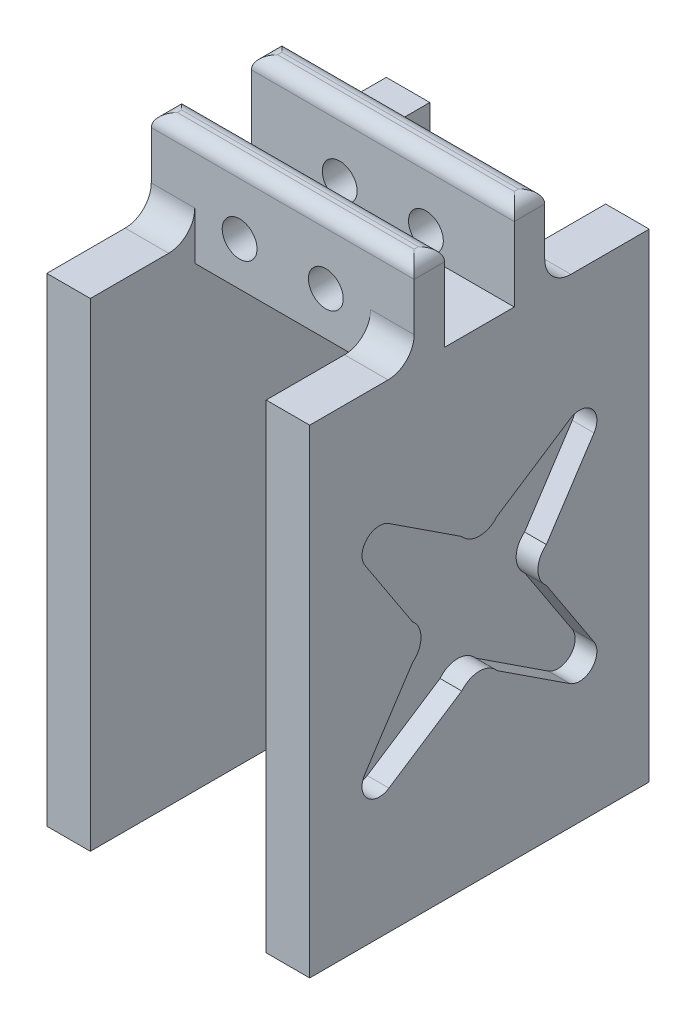
SolidWorks part; units mm, degrees
ref_plane "Front Plane" through (0, 0, 0) normal (0, 0, 1) x (1, 0, 0)
ref_plane "Top Plane" through (0, 0, 0) normal (0, 1, 0) x (1, 0, 0)
ref_plane "Right Plane" through (0, 0, 0) normal (1, 0, 0) x (0, 0, -1)
sketch "Sketch1" plane through (0, 0, 0) normal (1, 0, 0) x (0, 0, -1)
  line L0 (0, 27.5) -> (-4, 32.5) construction
  line L1 (-19.5, -27.5) -> (19.5, -27.5)
  line L2 (-19.5, -27.5) -> (-19.5, 27.5)
  line L3 (-19.5, 27.5) -> (-7.5, 27.5)
  line L4 (19.5, -27.5) -> (19.5, 27.5)
  line L5 (-19.5, -27.5) -> (19.5, 27.5) construction
  line L6 (-19.5, 27.5) -> (19.5, -27.5) construction
  line L8 (4, 27.5) -> (4, 37.5)
  line L9 (4, 37.5) -> (7.5, 37.5)
  line L10 (7.5, 27.5) -> (7.5, 37.5)
  line L12 (-4, 27.5) -> (-4, 37.5)
  line L13 (-4, 37.5) -> (-7.5, 37.5)
  line L14 (-7.5, 27.5) -> (-7.5, 37.5)
  line L15 (0, 27.5) -> (4, 32.5) construction
  line L16 (7.5, 27.5) -> (19.5, 27.5)
  line L17 (-4, 27.5) -> (4, 27.5)
  point P0 (0, 0)
  point P16 (-4.395, 37.5)
  point P18 (0, 0)
  point P19 (-0.3295, 28.4884)
  point P20 (0, 0)
  point P21 (3.6231, 37.5)
  dimension "D1" = 55
  dimension "D2" = 39
  dimension "D3" = 8
  dimension "D4" = 10
  dimension "D5" = 3.5
extrude "Boss-Extrude1" add sketch "Sketch1" along normal mid plane 30.2
sketch "Sketch2" plane through (0, 0, 19.5) normal (0, 0, 1) x (1, 0, 0)
  line L0 (15.1, -27.5) -> (-15.1, -27.5) construction
  line L1 (-10.1, -27.5) -> (10.1, -27.5)
  line L2 (-10.1, -27.5) -> (-10.1, 25)
  line L3 (-10.1, 25) -> (10.1, 25)
  line L4 (10.1, -27.5) -> (10.1, 25)
  line L5 (-10.1, -1.25) -> (-15.1, -1.25) construction
  line L6 (-15.1, 27.5) -> (-15.1, -27.5) construction
  line L7 (10.1, -1.25) -> (15.1, -1.25) construction
  line L8 (15.1, 27.5) -> (15.1, -27.5) construction
  dimension "D1" = 52.5
  dimension "D2" = 20.2
extrude "Cut-Extrude1" cut sketch "Sketch2" against normal up to surface (39 mm away) up to face at (0, 0, -19.5)
sketch "Sketch3" plane through (0, 27.5, 0) normal (0, 1, 0) x (1, 0, 0)
  line L0 (15.1, -19.5) -> (-15.1, -19.5) construction
  line L1 (-10.1, -19.5) -> (10.1, -19.5)
  line L2 (-10.1, -19.5) -> (-10.1, -7.5)
  line L3 (-10.1, -7.5) -> (10.1, -7.5)
  line L4 (10.1, -19.5) -> (10.1, -7.5)
  line L5 (15.1, -7.5) -> (-15.1, -7.5) construction
  line L6 (15.1, 7.5) -> (-15.1, 7.5) construction
  line L7 (-10.1, 7.5) -> (10.1, 7.5)
  line L8 (-10.1, 7.5) -> (-10.1, 19.5)
  line L9 (-10.1, 19.5) -> (10.1, 19.5)
  line L10 (10.1, 7.5) -> (10.1, 19.5)
  line L11 (15.1, 19.5) -> (-15.1, 19.5) construction
  line L12 (-10.1, -13.5) -> (-15.1, -13.5) construction
  line L13 (-15.1, -7.5) -> (-15.1, -19.5) construction
  line L14 (10.1, 13.5) -> (15.1, 13.5) construction
  line L15 (15.1, 19.5) -> (15.1, 7.5) construction
  line L16 (10.1, -13.5) -> (15.1, -13.5) construction
  line L17 (15.1, -7.5) -> (15.1, -19.5) construction
  line L18 (-10.1, 13.5) -> (-15.1, 13.5) construction
  line L19 (-15.1, 19.5) -> (-15.1, 7.5) construction
  dimension "D1" = 5
  dimension "D2" = 5
extrude "Cut-Extrude2" cut sketch "Sketch3" against normal up to surface (2.5 mm away) up to face at (0, 25, 0)
fillet "Fillet1" radius 3 4 edges at (-12.6, 27.5, -7.5) (12.6, 27.5, -7.5) (-12.6, 27.5, 7.5) (12.6, 27.5, 7.5)
fillet "Fillet2" radius 1.5 8 edges at (0, 37.5, -7.5) (15.1, 37.5, -5.75) (0, 37.5, -4) (-15.1, 37.5, -5.75) (0, 37.5, 4) (15.1, 37.5, 5.75) (0, 37.5, 7.5) (-15.1, 37.5, 5.75)
sketch "Sketch4" plane through (0, 0, 7.5) normal (0, 0, 1) x (1, 0, 0)
  line L0 (0, 36) -> (0, 25) construction
  line L1 (15.1, 36) -> (-15.1, 36) construction
  line L2 (-10.1, 25) -> (10.1, 25) construction
  circle A0 centre (-4.95, 30) radius 2
  circle A2 centre (4.95, 30) radius 2
  point P10 (0, 29.9804)
  dimension "D1" = 4
  dimension "D2" = 6
  dimension "D3" = 4.95
extrude "Cut-Extrude3" cut sketch "Sketch4" against normal up to surface (15 mm away) up to face at (0, 30.5, -7.5)
sketch "Sketch5" plane through (15.1, 0, 0) normal (1, 0, 0) x (0, 0, -1)
  line L0 (-12.9047, 12.9047) -> (12.9047, 12.9047) construction
  line L1 (0, 12.9047) -> (0, -12.9047) construction
  line L2 (12.9047, -12.9047) -> (-12.9047, -12.9047) construction
  line L3 (12.9047, 12.9047) -> (12.9047, -12.9047) construction
  line L4 (-7.6857, 2.0288) -> (-2.0288, 7.6857) construction
  line L5 (-12.9047, 12.9047) -> (12.9047, -12.9047) construction
  line L6 (-14.5654, 0) -> (12.9047, 0) construction
  line L7 (13.1637, 10.3949) -> (7.6857, 2.0288)
  line L8 (10.3949, 13.1637) -> (2.0288, 7.6857)
  line L9 (7.6857, 2.0288) -> (2.0288, 7.6857) construction
  line L10 (-13.1637, -10.3949) -> (-7.6857, -2.0288)
  line L11 (-10.3949, -13.1637) -> (-2.0288, -7.6857)
  line L12 (-10.3949, 13.1637) -> (-2.0288, 7.6857)
  line L13 (-13.1637, 10.3949) -> (-7.6857, 2.0288)
  line L14 (-12.9047, -12.9047) -> (12.9047, 12.9047) construction
  line L15 (10.3949, -13.1637) -> (2.0288, -7.6857)
  line L16 (13.1637, -10.3949) -> (7.6857, -2.0288)
  circle A0 centre (0, 0) radius 6.7175 construction
  arc A1 (-7.6857, 2.0288) -> (-7.6857, -2.0288) centre (-9.3273, 0) cw
  arc A2 (13.1637, -10.3949) -> (10.3949, -13.1637) centre (11.4905, -11.4905) cw
  arc A3 (-13.1637, 10.3949) -> (-10.3949, 13.1637) centre (-11.4905, 11.4905) cw
  arc A4 (13.1637, 10.3949) -> (10.3949, 13.1637) centre (11.4905, 11.4905) ccw
  arc A5 (7.6857, 2.0288) -> (7.6857, -2.0288) centre (9.3273, 0) ccw
  arc A6 (-13.1637, -10.3949) -> (-10.3949, -13.1637) centre (-11.4905, -11.4905) ccw
  arc A7 (2.0288, -7.6857) -> (-2.0288, -7.6857) centre (0, -9.3273) ccw
  arc A8 (2.0288, 7.6857) -> (-2.0288, 7.6857) centre (0, 9.3273) cw
  point P6 (12.9047, 0)
  point P7 (0, 12.9047)
  point P36 (-0.1638, -0.0117)
  point P37 (0, 0)
  point P39 (-19.5, 0)
  point P40 (-12.9047, 0)
  point P41 (-14.5654, 0)
  point P42 (0, 0)
  point P43 (12.9047, 0)
  point P44 (0, 0)
  point P45 (0, 0)
  point P46 (0, 0)
  point P47 (-9.571, 0)
  point P48 (-10.3139, 0)
  point P49 (-8.7656, 3.1088)
  point P50 (-10.5138, 10.5138)
  point P51 (-6.0354, 11.6923)
  point P52 (8.5611, 2.9042)
  point P53 (13.1072, 13.1072)
  point P54 (-3.6427, 9.2996)
  point P55 (-3.0983, 8.7552)
  point P56 (0, 6.7175)
  point P57 (6.7175, 0)
  point P58 (3.6239, 9.2807)
  point P59 (2.7026, 8.3594)
  point P60 (-2.8882, 8.545)
  point P61 (-10.4461, 13.2706)
  point P62 (-2.4745, 8.1314)
  point P63 (-2.7539, 8.4107)
  dimension "D4" = 9.5
  dimension "D5" = 2
  dimension "D1" = 36.5
  dimension "D2" = 8
  dimension "D3" = 90
  dimension "D6" = 10
extrude "Cut-Extrude4" cut sketch "Sketch5" against normal blind 2.5
sketch "Sketch6" plane through (-15.1, 0, 0) normal (-1, 0, 0) x (0, 0, 1)
  line L0 (-12.9047, 12.9047) -> (12.9047, 12.9047) construction
  line L1 (0, 12.9047) -> (0, -12.9047) construction
  line L2 (12.9047, -12.9047) -> (-12.9047, -12.9047) construction
  line L3 (12.9047, 12.9047) -> (12.9047, -12.9047) construction
  line L4 (-7.6857, 2.0288) -> (-2.0288, 7.6857) construction
  line L5 (-12.9047, 12.9047) -> (12.9047, -12.9047) construction
  line L6 (-9.0732, 0) -> (12.9047, 0) construction
  line L7 (13.1637, 10.3949) -> (7.6857, 2.0288)
  line L8 (10.3949, 13.1637) -> (2.0288, 7.6857)
  line L9 (7.6857, 2.0288) -> (2.0288, 7.6857) construction
  line L10 (-13.1637, -10.3949) -> (-7.6857, -2.0288)
  line L11 (-10.3949, -13.1637) -> (-2.0288, -7.6857)
  line L12 (-10.3949, 13.1637) -> (-2.0288, 7.6857)
  line L13 (-13.1637, 10.3949) -> (-7.6857, 2.0288)
  line L14 (-12.9047, -12.9047) -> (12.9047, 12.9047) construction
  line L15 (10.3949, -13.1637) -> (2.0288, -7.6857)
  line L16 (13.1637, -10.3949) -> (7.6857, -2.0288)
  circle A0 centre (0, 0) radius 6.7175 construction
  arc A1 (-7.6857, 2.0288) -> (-7.6857, -2.0288) centre (-9.3273, 0) cw
  arc A2 (13.1637, -10.3949) -> (10.3949, -13.1637) centre (11.4905, -11.4905) cw
  arc A3 (-13.1637, 10.3949) -> (-10.3949, 13.1637) centre (-11.4905, 11.4905) cw
  arc A4 (13.1637, 10.3949) -> (10.3949, 13.1637) centre (11.4905, 11.4905) ccw
  arc A5 (7.6857, 2.0288) -> (7.6857, -2.0288) centre (9.3273, 0) ccw
  arc A6 (-13.1637, -10.3949) -> (-10.3949, -13.1637) centre (-11.4905, -11.4905) ccw
  arc A7 (2.0288, -7.6857) -> (-2.0288, -7.6857) centre (0, -9.3273) ccw
  arc A8 (2.0288, 7.6857) -> (-2.0288, 7.6857) centre (0, 9.3273) cw
  point P6 (12.9047, 0)
  point P7 (0, 12.9047)
  point P36 (0, 6.7175)
  point P37 (6.7175, 0)
  point P38 (-0.9264, 0.287)
  point P39 (0, 0)
  dimension "D5" = 2
  dimension "D1" = 8
  dimension "D2" = 90
  dimension "D3" = 36.5
  dimension "D4" = 9.5
  dimension "D6" = 10
extrude "Cut-Extrude5" cut sketch "Sketch6" against normal blind 2.5
